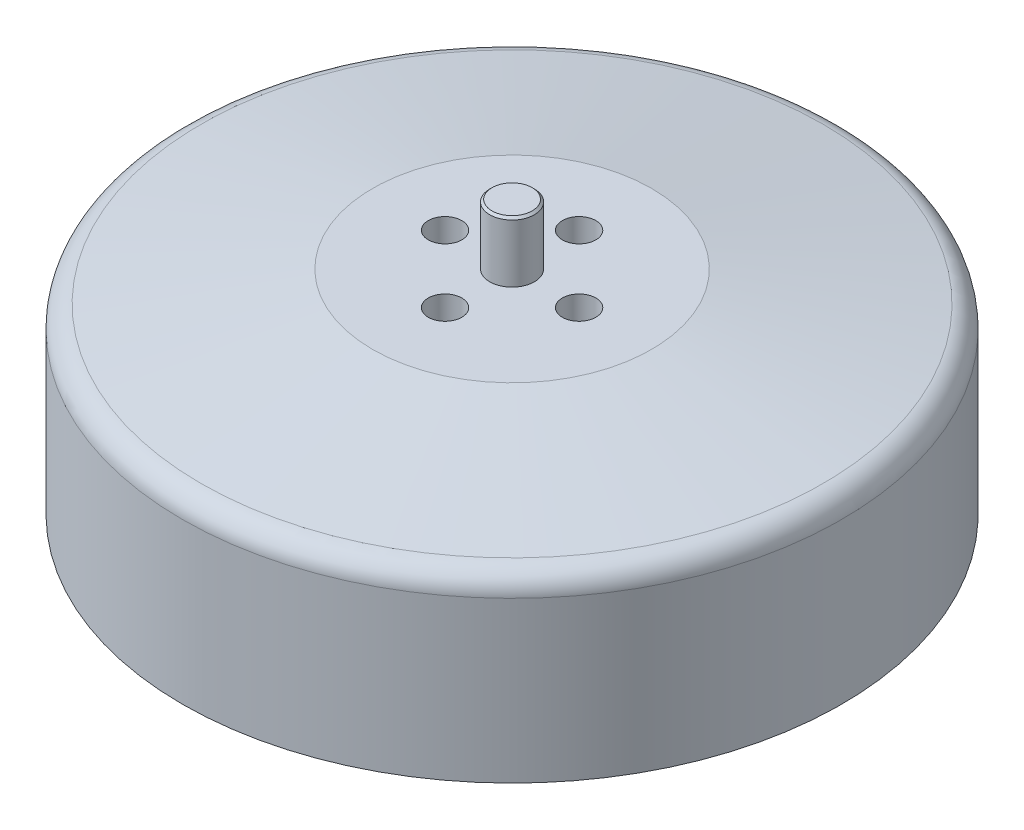
SolidWorks part; units mm, degrees
ref_plane "Front Plane" through (0, 0, 0) normal (0, 0, 1) x (1, 0, 0)
ref_plane "Top Plane" through (0, 0, 0) normal (0, 1, 0) x (1, 0, 0)
ref_plane "Right Plane" through (0, 0, 0) normal (1, 0, 0) x (0, 0, -1)
sketch "Sketch1" plane through (0, 0, 0) normal (0, 1, 0) x (1, 0, 0)
  circle A0 centre (0, 0) radius 29.5
  circle A1 centre (0, 0) radius 27.5
  dimension "D2" = 59
  dimension "D1" = 55
extrude "Boss-Extrude2" add sketch "Sketch1" along normal blind 14
sketch "Sketch3" plane through (0, 14, 0) normal (0, 1, 0) x (1, 0, 0)
  line L0 (0, 0) -> (0, 6) construction
  circle A0 centre (0, 6) radius 1.5
  circle A1 centre (6, 0) radius 1.5
  circle A2 centre (0, -6) radius 1.5
  circle A3 centre (-6, 0) radius 1.5
  circle A4 centre (0, 0) radius 29.5
  point P13 (0, 0)
  dimension "D1" = 6
  dimension "D2" = 3
  dimension "D3" = 4
extrude "Boss-Extrude3" add sketch "Sketch3" along normal blind 5
chamfer "Chamfer1" distance 3 angle 80 1 edges at (0, 19, 29.5)
fillet "Fillet1" radius 2 1 edges at (0, 16, 29.5)
sketch "Sketch4" plane through (0, 19, 0) normal (0, 1, 0) x (1, 0, 0)
  circle A0 centre (0, 0) radius 2
  dimension "D1" = 4
extrude "Boss-Extrude4" add sketch "Sketch4" along normal blind 5.4
chamfer "Chamfer2" distance 0.2 angle 45 1 edges at (0, 24.4, 2)
